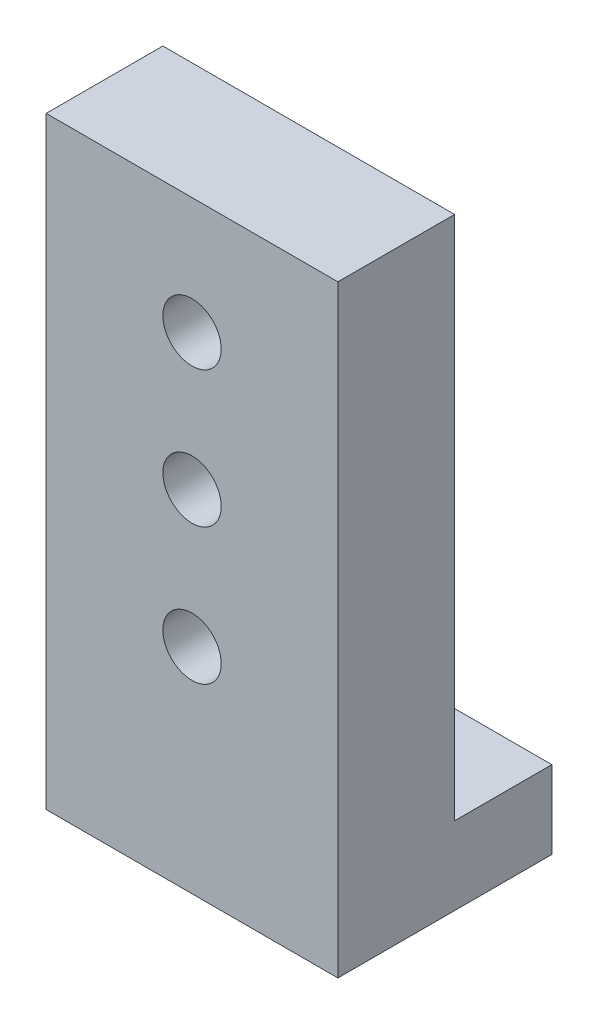
SolidWorks part; units mm, degrees
ref_plane "Front Plane" through (0, 0, 0) normal (0, 0, 1) x (1, 0, 0)
ref_plane "Top Plane" through (0, 0, 0) normal (0, 1, 0) x (1, 0, 0)
ref_plane "Right Plane" through (0, 0, 0) normal (1, 0, 0) x (0, 0, -1)
sketch "Sketch1" plane through (0, 0, 0) normal (0, 0, 1) x (1, 0, 0)
  line L1 (-7.5, -15.5) -> (7.5, -15.5)
  line L2 (-7.5, -15.5) -> (-7.5, 15.5)
  line L3 (-7.5, 15.5) -> (7.5, 15.5)
  line L4 (7.5, -15.5) -> (7.5, 15.5)
  line L5 (-7.5, -15.5) -> (7.5, 15.5) construction
  line L6 (-7.5, 15.5) -> (7.5, -15.5) construction
  point P0 (0, 0)
  dimension "D1" = 31
  dimension "D2" = 15
extrude "Boss-Extrude1" add sketch "Sketch1" along normal blind 6
sketch "Sketch2" plane through (0, 0, 6) normal (0, 0, 1) x (1, 0, 0)
  line L0 (7.5, 15.5) -> (-7.5, 15.5) construction
  circle A0 centre (0, 9.5) radius 1.5
  circle A1 centre (0, 2.5) radius 1.5
  circle A2 centre (0, -4.5) radius 1.5
  dimension "D1" = 3
  dimension "D2" = 6
  dimension "D3" = 3
extrude "Cut-Extrude1" cut sketch "Sketch2" against normal blind 6
sketch "Sketch3" plane through (0, 0, 0) normal (0, 0, -1) x (-1, 0, 0)
  line L0 (-7.5, -15.5) -> (-7.5, -11.5)
  line L1 (-7.5, -15.5) -> (-7.5, 15.5) construction
  line L2 (-7.5, -11.5) -> (7.5, -11.5)
  line L3 (7.5, 15.5) -> (7.5, -15.5) construction
  line L4 (7.5, -11.5) -> (7.5, -15.5)
  line L5 (7.5, -15.5) -> (-7.5, -15.5)
  dimension "D1" = 4
extrude "Boss-Extrude2" add sketch "Sketch3" along normal blind 5
